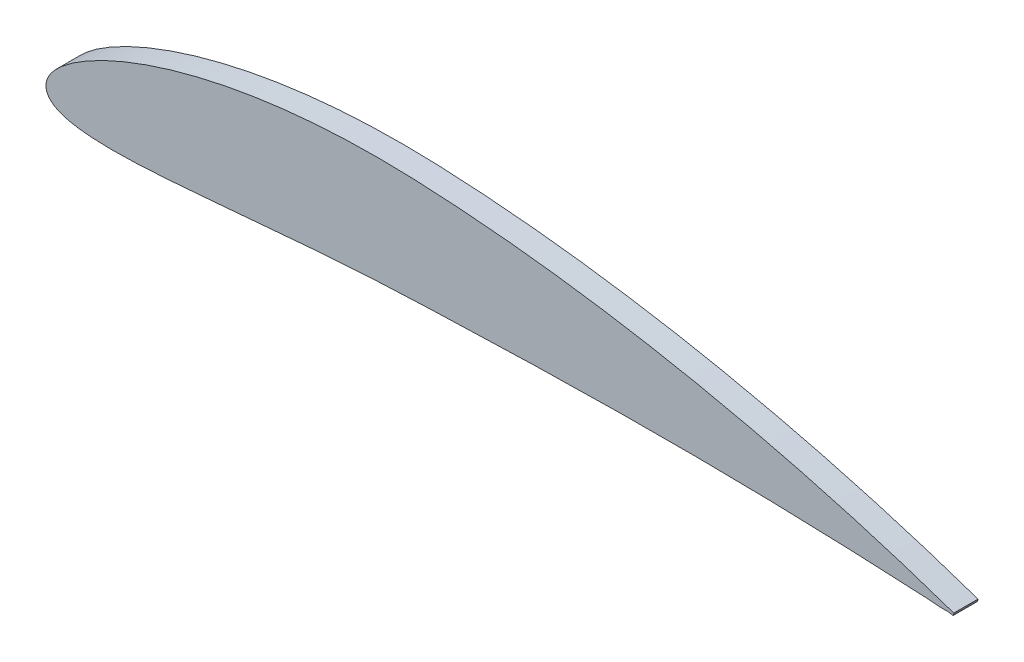
SolidWorks part; units mm, degrees
ref_plane "Front Plane" through (0, 0, 0) normal (0, 0, 1) x (1, 0, 0)
ref_plane "Top Plane" through (0, 0, 0) normal (0, 1, 0) x (1, 0, 0)
ref_plane "Right Plane" through (0, 0, 0) normal (1, 0, 0) x (0, 0, -1)
curve "Curve3"
  spline degree 3 poles (1000.25, 1.24, 0) (999.36, 1.5466, 0) (995.8139, 2.7683, 0) (987.8762, 5.5077, 0) (974.7136, 9.9275, 0) (956.465, 15.9446, 0) (933.2861, 23.3123, 0) (905.3935, 31.8009, 0) (873.0611, 41.1442, 0) (836.5996, 51.0483, 0) (796.3762, 61.2143, 0) (752.7953, 71.3209, 0) (706.3231, 81.1144, 0) (657.4446, 90.2776, 0) (606.6871, 98.541, 0) (554.6079, 105.6901, 0) (501.792, 111.4952, 0) (448.8062, 115.7722, 0) (395.8896, 118.5809, 0) (343.6082, 118.9114, 0) (292.6925, 116.357, 0) (244.199, 111.1728, 0) (198.7693, 103.6648, 0) (157.0012, 94.1608, 0) (119.4181, 83.1247, 0) (86.4596, 71.0512, 0) (58.48, 58.4287, 0) (35.7445, 45.7437, 0) (18.354, 33.4445, 0) (6.4016, 21.7983, 0) (-0.4785, 10.7687, 0) (-1.1021, -0.3322, 0) (5.4783, -9.2258, 0) (17.0143, -14.7948, 0) (32.8747, -18.4511, 0) (53.3085, -20.3675, 0) (78.1118, -20.7512, 0) (107.0475, -19.7633, 0) (139.7896, -17.6475, 0) (176.0022, -14.654, 0) (215.3329, -11.125, 0) (257.4273, -7.3624, 0) (301.9209, -3.6922, 0) (348.4441, -0.4557, 0) (396.9816, 1.9832, 0) (447.1013, 3.7059, 0) (498.2783, 5.4818, 0) (549.6221, 6.9005, 0) (600.5599, 7.9279, 0) (650.5484, 8.5041, 0) (699.0372, 8.6069, 0) (745.4858, 8.2663, 0) (789.3705, 7.5598, 0) (830.1852, 6.5089, 0) (867.4516, 5.2968, 0) (900.7439, 3.9432, 0) (929.5972, 2.6539, 0) (953.857, 1.2862, 0) (972.6764, 0.624, 0) (987.1696, -1.0584, 0) (994.3521, -0.0144, 0) (999.8798, -2.0481, 0) (999.9716, -0.4847, 0) (1000, 0, 0) knots 0 0 0 0 0.001372 0.005465 0.012235 0.021602 0.033461 0.047671 0.064081 0.082496 0.102719 0.124527 0.147676 0.171913 0.196978 0.222597 0.248497 0.274385 0.300041 0.32569 0.350525 0.37428 0.396711 0.417577 0.436654 0.453744 0.46868 0.481329 0.491631 0.499616 0.505546 0.510185 0.514824 0.520702 0.528516 0.538466 0.550543 0.564643 0.580638 0.598345 0.617584 0.638174 0.659922 0.682632 0.706121 0.730727 0.7557 0.780732 0.805564 0.829932 0.85357 0.876213 0.89761 0.917519 0.935698 0.951943 0.966047 0.97784 0.987174 0.993932 0.998018 0.999386 1 1 1 1
sketch "Sketch4" plane through (0, 0, 0) normal (0, 0, 1) x (1, 0, 0)
  line L0 (161.8916, 43.8587) -> (11.8916, 44.5158) construction
  line L1 (11.8916, 44.5158) -> (12.3467, 148.3867) construction
  line L2 (161.8916, 43.8587) -> (161.9291, 44.0446)
  spline S1 degree 3 poles (161.9291, 44.0446) (161.7957, 44.0906) (161.2641, 44.2737) (160.0741, 44.6844) (158.1009, 45.3469) (155.3653, 46.249) (151.8905, 47.3535) (147.7092, 48.626) (142.8622, 50.0266) (137.3963, 51.5114) (131.3664, 53.0353) (124.8332, 54.5504) (117.8665, 56.0186) (110.5392, 57.3922) (102.9301, 58.631) (95.1229, 59.7027) (87.2053, 60.573) (79.2622, 61.2141) (71.3295, 61.6352) (63.492, 61.6847) (55.8592, 61.3018) (48.5895, 60.5246) (41.7792, 59.3991) (35.5177, 57.9744) (29.8836, 56.3199) (24.9428, 54.51) (20.7484, 52.6178) (17.3401, 50.7162) (14.7331, 48.8724) (12.9413, 47.1265) (11.9099, 45.4731) (11.8164, 43.8089) (12.8029, 42.4757) (14.5323, 41.6408) (16.9099, 41.0927) (19.9731, 40.8054) (23.6914, 40.7479) (28.0291, 40.896) (32.9375, 41.2132) (38.3661, 41.6619) (44.2622, 42.191) (50.5726, 42.755) (57.2426, 43.3052) (64.2169, 43.7904) (71.4932, 44.156) (79.0066, 44.4143) (86.6785, 44.6805) (94.3755, 44.8932) (102.0116, 45.0472) (109.5054, 45.1336) (116.7743, 45.149) (123.7374, 45.0979) (130.3162, 44.992) (136.4347, 44.8345) (142.0213, 44.6528) (147.0121, 44.4498) (151.3375, 44.2566) (154.9743, 44.0515) (157.7955, 43.9523) (159.9682, 43.7001) (161.0449, 43.8566) (161.8736, 43.5517) (161.8874, 43.7861) (161.8916, 43.8587) knots 0 0 0 0 0.001372 0.005465 0.012235 0.021602 0.033461 0.047671 0.064081 0.082496 0.102719 0.124527 0.147676 0.171913 0.196978 0.222597 0.248497 0.274385 0.300041 0.32569 0.350525 0.37428 0.396711 0.417577 0.436654 0.453744 0.46868 0.481329 0.491631 0.499616 0.505546 0.510185 0.514824 0.520702 0.528516 0.538466 0.550543 0.564643 0.580638 0.598345 0.617584 0.638174 0.659922 0.682632 0.706121 0.730727 0.7557 0.780732 0.805564 0.829932 0.85357 0.876213 0.89761 0.917519 0.935698 0.951943 0.966047 0.97784 0.987174 0.993932 0.998018 0.999386 1 1 1 1
  dimension "D1" = 150
extrude "Boss-Extrude1" add sketch "Sketch4" along normal blind 4
sketch "Sketch6" plane through (0, 0, 0) normal (0, 1, 0) x (1, 0, 0)
  line L1 (161.9291, -2) -> (11.8916, -2) construction
  line L2 (11.8916, 0) -> (11.8916, -4) construction
sketch "Sketch7" plane through (0, 0, 0) normal (0, 1, 0) x (1, 0, 0)
  line L1 (-222.2373, 130.1141) -> (492.88, 130.1141)
  line L2 (-222.2373, 130.1141) -> (-222.2373, -1063.571)
  line L3 (-222.2373, -1063.571) -> (492.88, -1063.571)
  line L4 (492.88, 130.1141) -> (492.88, -1063.571)
sketch "Sketch8" plane through (0, 0, 0) normal (0, 1, 0) x (1, 0, 0)
  line L1 (0, -1049.128) -> (174.1208, -1049.128)
  line L2 (0, -1049.128) -> (0, -1092.0274)
  line L3 (0, -1092.0274) -> (174.1208, -1092.0274)
  line L4 (174.1208, -1049.128) -> (174.1208, -1092.0274)
sketch "Sketch9" plane through (0, 0, 0) normal (0, 1, 0) x (1, 0, 0)
  line L1 (1.775, -1075.8163) -> (183.1621, -1075.8163)
  line L2 (1.775, -1075.8163) -> (1.775, -1103.1662)
  line L3 (1.775, -1103.1662) -> (183.1621, -1103.1662)
  line L4 (183.1621, -1075.8163) -> (183.1621, -1103.1662)
sketch "Sketch10" plane through (0, 0, 4) normal (0, 0, 1) x (1, 0, 0)
  circle A0 centre (38.8025, 49.9556) radius 3
  dimension "D1" = 6
sketch "Sketch12" plane through (0, 0, 4) normal (0, 0, 1) x (1, 0, 0)
  circle A0 centre (71.9431, 52.4166) radius 3
  dimension "D1" = 6
